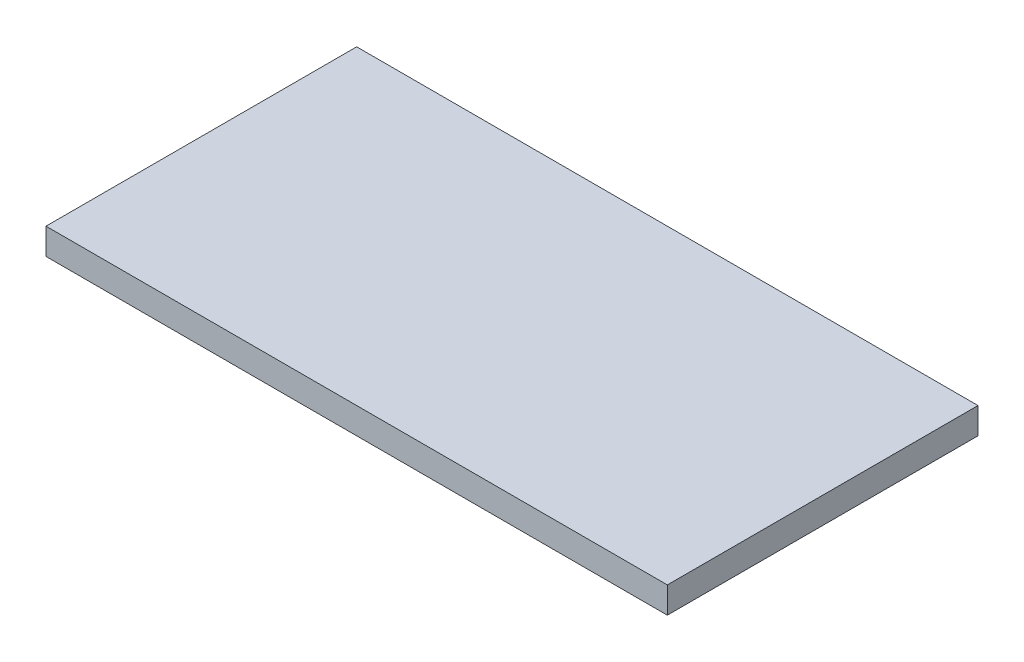
SolidWorks part; units mm, degrees
ref_plane "Front Plane" through (0, 0, 0) normal (0, 0, 1) x (1, 0, 0)
ref_plane "Top Plane" through (0, 0, 0) normal (0, 1, 0) x (1, 0, 0)
ref_plane "Right Plane" through (0, 0, 0) normal (1, 0, 0) x (0, 0, -1)
sketch "Sketch1" plane through (0, 0, 0) normal (0, 1, 0) x (1, 0, 0)
  line L1 (-50.9, 25.45) -> (50.9, 25.45)
  line L2 (-50.9, 25.45) -> (-50.9, -25.45)
  line L3 (-50.9, -25.45) -> (50.9, -25.45)
  line L4 (50.9, 25.45) -> (50.9, -25.45)
  line L5 (-50.9, 25.45) -> (50.9, -25.45) construction
  line L6 (-50.9, -25.45) -> (50.9, 25.45) construction
  point P4 (0, 0)
  point P5 (0, 0)
  dimension "D1" = 101.8
  dimension "D2" = 50.9
extrude "Boss-Extrude1" add sketch "Sketch1" along normal blind 4.3
